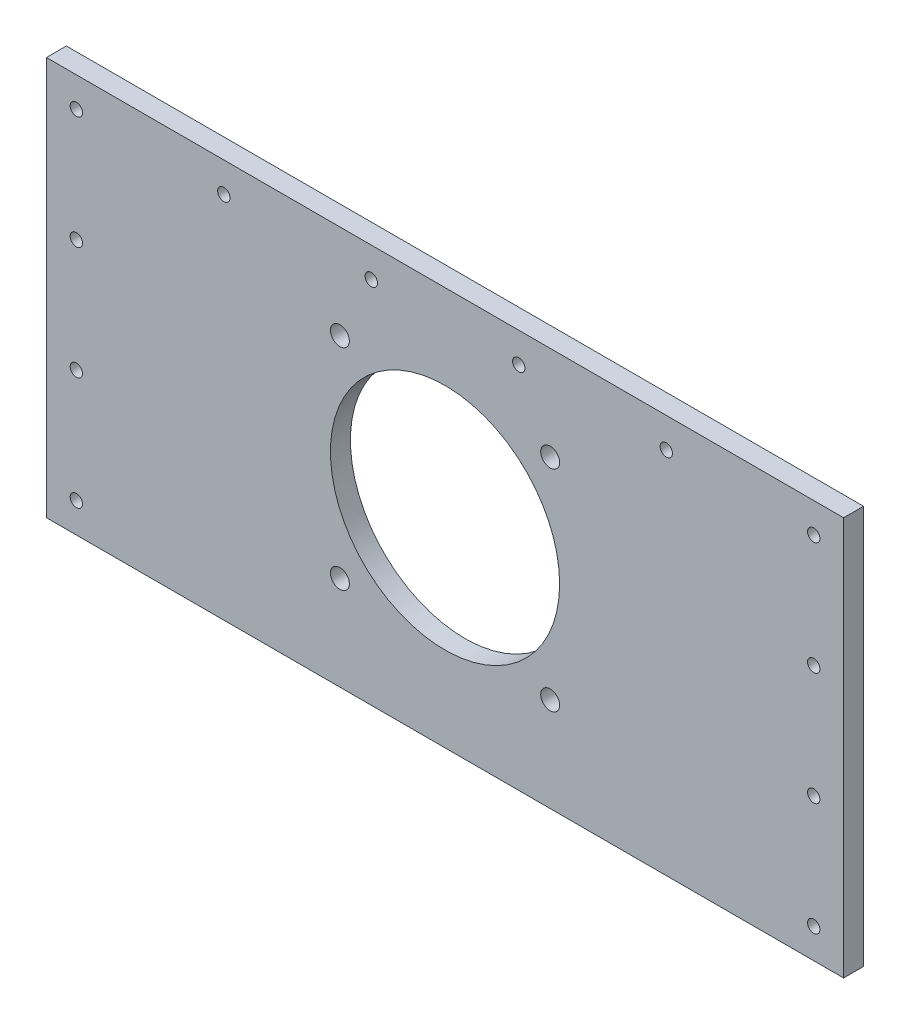
SolidWorks part; units mm, degrees
ref_plane "Front Plane" through (0, 0, 0) normal (0, 0, 1) x (1, 0, 0)
ref_plane "Top Plane" through (0, 0, 0) normal (0, 1, 0) x (1, 0, 0)
ref_plane "Right Plane" through (0, 0, 0) normal (1, 0, 0) x (0, 0, -1)
sketch "Sketch1" plane through (0, 0, 0) normal (0, 0, 1) x (1, 0, 0)
  line L1 (-200, -100) -> (200, -100)
  line L2 (-200, -100) -> (-200, 100)
  line L3 (-200, 100) -> (200, 100)
  line L4 (200, -100) -> (200, 100)
  line L5 (-200, -100) -> (200, 100) construction
  line L6 (-200, 100) -> (200, -100) construction
  line L7 (-52.7572, -52.7572) -> (52.7572, -52.7572) construction
  line L8 (-52.7572, -52.7572) -> (-52.7572, 52.7572) construction
  line L9 (-52.7572, 52.7572) -> (52.7572, 52.7572) construction
  line L10 (52.7572, -52.7572) -> (52.7572, 52.7572) construction
  line L11 (-52.7572, -52.7572) -> (52.7572, 52.7572) construction
  line L12 (-52.7572, 52.7572) -> (52.7572, -52.7572) construction
  circle A0 centre (0, 0) radius 74.61 construction
  circle A1 centre (-52.7572, 52.7572) radius 4.75
  circle A2 centre (52.7572, 52.7572) radius 4.75
  circle A3 centre (52.7572, -52.7572) radius 4.75
  circle A4 centre (-52.7572, -52.7572) radius 4.75
  circle A5 centre (0, 0) radius 57.5
  point P0 (0, 0)
  dimension "D1" = 149.22
  dimension "D3" = 9.5
  dimension "D4" = 115
  dimension "D2" = 200
  dimension "D5" = 400
extrude "Boss-Extrude1" add sketch "Sketch1" along normal blind 10
sketch "Sketch2" plane through (0, 0, 10) normal (0, 0, 1) x (1, 0, 0)
  line L0 (-185, -100) -> (-185, 100) construction
  line L1 (-200, -100) -> (200, -100) construction
  line L2 (200, 100) -> (-200, 100) construction
  line L3 (-200, 85) -> (200, 85) construction
  line L4 (-200, 100) -> (-200, -100) construction
  line L5 (200, -100) -> (200, 100) construction
  line L6 (0, -100) -> (0, 100) construction
  line L7 (185, -100) -> (185, 100) construction
  line L8 (-185, 85) -> (-111, 85) construction
  circle A0 centre (-185, 85) radius 3.1
  circle A1 centre (-185, 28.3333) radius 3.1
  circle A2 centre (-185, -85) radius 3.1
  circle A3 centre (-185, -28.3333) radius 3.1
  circle A4 centre (185, -28.3333) radius 3.1
  circle A5 centre (185, -85) radius 3.1
  circle A6 centre (185, 28.3333) radius 3.1
  circle A7 centre (185, 85) radius 3.1
  circle A8 centre (-111, 85) radius 3.1
  circle A9 centre (-37, 85) radius 3.1
  circle A10 centre (37, 85) radius 3.1
  circle A11 centre (111, 85) radius 3.1
  dimension "D5" = 6.2
  dimension "D1" = 15
  dimension "D2" = 15
  dimension "D3" = 15
  dimension "D4" = 15
  dimension "D6" = 56.6667
  dimension "D7" = 56.6667
  dimension "D8" = 5
  dimension "D9" = 74
extrude "Cut-Extrude1" cut sketch "Sketch2" against normal blind 10
